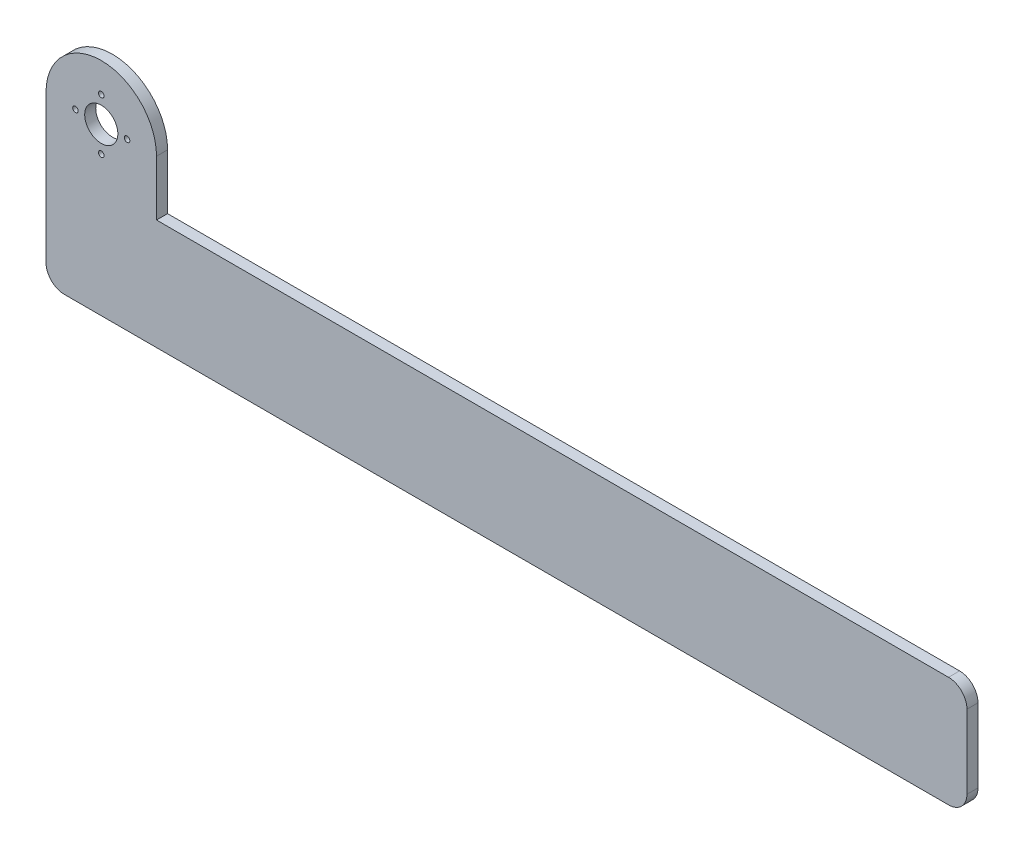
SolidWorks part; units mm, degrees
material "Aleación 1060"
ref_plane "Alzado" through (0, 0, 0) normal (0, 0, 1) x (1, 0, 0)
ref_plane "Planta" through (0, 0, 0) normal (0, 1, 0) x (1, 0, 0)
ref_plane "Vista lateral" through (0, 0, 0) normal (1, 0, 0) x (0, 0, -1)
sketch "Croquis1" plane through (0, 0, 0) normal (0, 0, 1) x (1, 0, 0)
  line L0 (30, -45) -> (470, -45)
  line L2 (-30, 45) -> (-30, -45)
  line L3 (-30, -45) -> (30, -45)
  line L4 (30, 45) -> (30, 15)
  line L5 (-30, 45) -> (30, -45) construction
  line L6 (-30, -45) -> (30, 45) construction
  line L7 (470, -45) -> (470, 15)
  line L8 (470, 15) -> (30, 15)
  arc A0 (-30, 45) -> (30, 45) centre (0, 45) cw
  point P0 (0, 0)
  dimension "D1" = 90
  dimension "6" = 30
  dimension "D2" = 60
  dimension "D3" = 500
  dimension "D4" = 30
extrude "Saliente-Extruir1" add sketch "Croquis1" against normal blind 6
fillet "Redondeo1" radius 10 1 edges at (-30, -45, -3)
fillet "Redondeo2" radius 10 2 edges at (470, -45, -3) (470, 15, -3)
sketch "Croquis2" plane through (0, 0, -6) normal (0, 0, -1) x (-1, 0, 0)
  circle A0 centre (0, 45) radius 9
  dimension "D1" = 18
extrude "Cortar-Extruir1" cut sketch "Croquis2" against normal through all
sketch "Croquis3" plane through (0, 0, -6) normal (0, 0, -1) x (-1, 0, 0)
  line L1 (30, 45) -> (30, -35) construction
  circle A0 centre (0, 31) radius 1.5
  circle A1 centre (14, 45) radius 1.5
  circle A2 centre (0, 59) radius 1.5
  circle A3 centre (-14, 45) radius 1.5
  dimension "D2" = 3
  dimension "D4" = 3
  dimension "D5" = 3
  dimension "D8" = 3
  dimension "D1" = 14
  dimension "D3" = 14
  dimension "D6" = 14
  dimension "D7" = 14
  dimension "D10" = 30
extrude "Cortar-Extruir2" cut sketch "Croquis3" against normal through all
